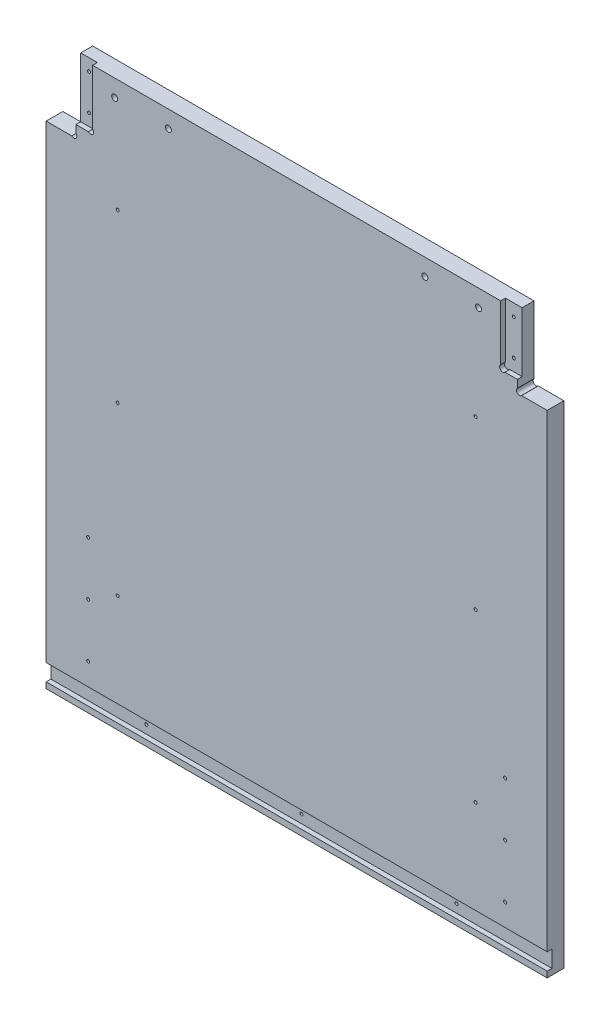
SolidWorks part; units mm, degrees
material "Pine"
ref_plane "Front Plane" through (0, 0, 0) normal (0, 0, 1) x (1, 0, 0)
ref_plane "Top Plane" through (0, 0, 0) normal (0, 1, 0) x (1, 0, 0)
ref_plane "Right Plane" through (0, 0, 0) normal (1, 0, 0) x (0, 0, -1)
sketch "Sketch1" plane through (0, 0, 0) normal (0, 0, 1) x (1, 0, 0)
  line L0 (8932.6508, -5243.5125) -> (10226.1458, -5243.5125)
  line L1 (9086.3208, -4722.0918) -> (10222.9708, -4853.7812)
  line L2 (8914.8708, -6342.0625) -> (10197.5708, -6342.0625)
  line L3 (8914.8708, -5808.6625) -> (10197.5708, -5808.6625)
  line L4 (8919.6333, -5253.0375) -> (10218.2083, -5253.0375)
  line L5 (9134.2633, -4656.1375) -> (9134.2633, -4638.3575)
  line L6 (9091.0833, -4638.3575) -> (9134.2633, -4638.3575)
  line L7 (9091.0833, -4567.2375) -> (9091.0833, -4638.3575)
  line L8 (9134.2633, -4656.1375) -> (9581.3033, -4656.1375)
  line L9 (9091.0833, -4567.2375) -> (9624.4833, -4567.2375)
  line L10 (9581.3033, -4656.1375) -> (9581.3033, -4638.3575)
  line L11 (9581.3033, -4638.3575) -> (9624.4833, -4638.3575)
  line L12 (9624.4833, -4567.2375) -> (9624.4833, -4638.3575)
  line L13 (8932.6508, -5225.7325) -> (9344.9775, -5225.7325)
  line L14 (8932.6508, -5256.2125) -> (8932.6508, -5243.5125)
  line L15 (8911.6958, -5256.2125) -> (8932.6508, -5256.2125)
  line L16 (8914.8708, -4722.0918) -> (9086.3208, -4722.0918)
  line L17 (8911.6958, -4715.5913) -> (8932.6508, -4715.5913)
  line L18 (8914.8708, -6342.0625) -> (8914.8708, -5808.6625)
  line L19 (12082.9917, -4722.0918) -> (10946.3417, -4853.7812)
  line L20 (12236.6617, -5243.5125) -> (10943.1667, -5243.5125)
  line L21 (10951.1042, -5253.0375) -> (12249.6792, -5253.0375)
  line L22 (10838.3917, -5656.2625) -> (11308.2917, -5656.2625)
  line L23 (10838.3917, -5719.7625) -> (11308.2917, -5719.7625)
  line L24 (10838.3917, -5742.5368) -> (11308.2917, -5742.5368)
  line L25 (10806.6417, -6342.0625) -> (11340.0417, -6342.0625)
  line L26 (10803.4667, -6335.7125) -> (11343.2167, -6335.7125)
  line L27 (10803.4667, -6317.9325) -> (11343.2167, -6317.9325)
  line L28 (10943.1667, -5225.7325) -> (11376.4483, -5225.7325)
  line L29 (11506.7292, -4754.5625) -> (10806.6417, -4827.5875)
  line L30 (11506.7292, -4567.2375) -> (11506.7292, -4754.5625)
  line L31 (10806.6417, -4567.2375) -> (10806.6417, -4827.5875)
  line L32 (10806.6417, -4567.2375) -> (11506.7292, -4567.2375)
  line L33 (10235.6708, -6329.3625) -> (10245.1958, -6329.3625)
  line L34 (10245.1958, -6329.3625) -> (10254.7208, -6278.5625)
  line L35 (10302.3458, -6329.3625) -> (10311.8708, -6278.5625)
  line L36 (10302.3458, -6329.3625) -> (10292.8208, -6329.3625)
  line L37 (10245.1958, -5821.3625) -> (10254.7208, -5872.1625)
  line L38 (10235.6708, -5821.3625) -> (10245.1958, -5821.3625)
  line L39 (10292.8208, -5821.3625) -> (10302.3458, -5821.3625)
  line L40 (10302.3458, -5821.3625) -> (10311.8708, -5872.1625)
  line L41 (10235.6708, -5821.3625) -> (10235.6708, -6329.3625)
  line L42 (10254.7208, -5872.1625) -> (10254.7208, -6278.5625)
  line L43 (10311.8708, -5872.1625) -> (10311.8708, -6278.5625)
  line L44 (10292.8208, -5821.3625) -> (10292.8208, -6329.3625)
  line L45 (8932.6508, -5225.7325) -> (8932.6508, -4715.5913)
  line L46 (8911.6958, -4715.5913) -> (8911.6958, -5256.2125)
  line L47 (8914.8708, -5248.275) -> (8914.8708, -4722.0918)
  line L48 (8919.6333, -5253.0375) -> (8914.8708, -5248.275)
  line L49 (8914.8708, -5145.0875) -> (8937.426, -5145.0875)
  line L50 (8914.8708, -5202.2375) -> (8937.426, -5202.2375)
  line L51 (10838.3917, -5656.2625) -> (10838.3917, -5719.7625)
  line L52 (10832.0417, -5736.1868) -> (10856.1717, -5736.1868)
  line L53 (10806.6417, -6342.0625) -> (10806.6417, -5818.7368)
  line L54 (10832.0417, -5649.9125) -> (10856.1717, -5649.9125)
  line L55 (10832.0417, -5726.1125) -> (10856.1717, -5726.1125)
  line L56 (10806.6417, -5818.7368) -> (10833.9015, -5818.7368)
  line L57 (10832.0417, -5806.0442) -> (10851.6815, -5806.0442)
  line L58 (10856.1717, -5801.5541) -> (10856.1717, -5736.1868)
  line L59 (10838.3917, -5814.2467) -> (10838.3917, -5742.5368)
  line L60 (10832.0417, -5806.0442) -> (10832.0417, -5736.1868)
  line L61 (10803.4667, -6317.9325) -> (10803.4667, -6335.7125)
  line L62 (10197.5708, -5808.6625) -> (10197.5708, -6342.0625)
  line L63 (9762.3842, -6348.4125) -> (9762.3842, -5802.3125)
  line L64 (9780.1642, -6348.4125) -> (9762.3842, -6348.4125)
  line L65 (9780.1642, -5802.3125) -> (9780.1642, -6348.4125)
  line L66 (9762.3842, -5802.3125) -> (9780.1642, -5802.3125)
  line L67 (9332.2775, -6348.4125) -> (9332.2775, -5802.3125)
  line L68 (9332.2775, -6348.4125) -> (9350.0575, -6348.4125)
  line L69 (9350.0575, -5802.3125) -> (9350.0575, -6348.4125)
  line L70 (9332.2775, -5802.3125) -> (9350.0575, -5802.3125)
  line L71 (9993.8374, -6061.075) -> (9993.8374, -6045.2418)
  line L72 (9998.5999, -6065.8375) -> (10014.4331, -6065.8375)
  line L73 (9998.5999, -6084.8875) -> (10014.4331, -6084.8875)
  line L74 (9993.8374, -6105.4832) -> (9993.8374, -6089.65)
  line L75 (9974.7874, -6105.4832) -> (9974.7874, -6089.65)
  line L76 (9954.1917, -6084.8875) -> (9970.0249, -6084.8875)
  line L77 (9974.7874, -6061.075) -> (9974.7874, -6045.2418)
  line L78 (9954.1917, -6065.8375) -> (9970.0249, -6065.8375)
  line L79 (10793.9417, -6237.2875) -> (10816.4969, -6237.2875)
  line L80 (10793.9417, -6294.4375) -> (10816.4969, -6294.4375)
  line L81 (10856.1717, -5649.9125) -> (10856.1717, -5726.1125)
  line L82 (10832.0417, -5726.1125) -> (10832.0417, -5649.9125)
  line L83 (10226.1458, -5225.7325) -> (10226.1458, -5243.5125)
  line L84 (10205.1908, -5257.8) -> (10205.1908, -4844.2499)
  line L85 (10230.9083, -4844.2499) -> (10230.9083, -5257.8)
  line L86 (10205.1908, -5257.8) -> (10230.9083, -5257.8)
  line L87 (10205.1908, -4844.2499) -> (10230.9083, -4844.2499)
  line L88 (10946.3417, -5176.8375) -> (10968.8969, -5176.8375)
  line L89 (9349.4676, -5141.9125) -> (9358.2674, -5141.9125)
  line L90 (10946.3417, -5119.6875) -> (10968.8969, -5119.6875)
  line L91 (9929.011, -4660.9635) -> (10066.0807, -4660.9635)
  line L92 (9929.011, -4678.7435) -> (10066.0807, -4678.7435)
  line L93 (10943.1667, -5225.7325) -> (10943.1667, -5243.5125)
  line L94 (10946.3417, -5248.275) -> (10951.1042, -5253.0375)
  line L95 (10946.3417, -5257.8063) -> (10946.3417, -4849.0188)
  line L96 (10964.1217, -5257.8) -> (10964.1217, -4844.2499)
  line L97 (10938.4042, -4844.2499) -> (10938.4042, -5257.8)
  line L98 (10938.4042, -5257.8) -> (10964.1217, -5257.8)
  line L99 (10964.1217, -4844.2499) -> (10938.4042, -4844.2499)
  line L100 (10344.8908, -4560.8875) -> (10369.0208, -4560.8875)
  line L101 (10344.8908, -4560.8875) -> (10369.0208, -4560.8875)
  line L102 (10800.2917, -4560.8875) -> (10824.4217, -4560.8875)
  line L103 (10200.4156, -5119.6875) -> (10222.9708, -5119.6875)
  line L104 (10200.4156, -5176.8375) -> (10222.9708, -5176.8375)
  line L105 (9344.9775, -5146.4026) -> (9344.9775, -5225.7325)
  line L106 (10344.8908, -4560.8875) -> (10344.8908, -4833.9375)
  line L107 (9792.8642, -5225.7325) -> (9792.8642, -5146.4026)
  line L108 (9362.7575, -5225.7325) -> (9775.0842, -5225.7325)
  line L109 (9680.3633, -4761.8396) -> (9680.3633, -4559.9604)
  line L110 (9656.2333, -4559.9604) -> (9680.3633, -4559.9604)
  line L111 (9656.2333, -4761.8396) -> (9680.3633, -4761.8396)
  line L112 (9656.2333, -4761.8396) -> (9656.2333, -4559.9604)
  line L113 (9779.5743, -5141.9125) -> (9788.374, -5141.9125)
  line L114 (10070.5708, -4665.4536) -> (10070.5708, -4674.2534)
  line L115 (9924.5208, -4674.2534) -> (9924.5208, -4665.4536)
  line L116 (12127.4417, -6188.3925) -> (12205.5015, -6188.3925)
  line L117 (12209.9917, -6170.6125) -> (12209.9917, -6183.9024)
  line L118 (9792.8642, -5225.7325) -> (10226.1458, -5225.7325)
  line L119 (9662.5833, -4754.5625) -> (10362.6708, -4827.5875)
  line L120 (9662.5833, -4567.2375) -> (9662.5833, -4754.5625)
  line L121 (10362.6708, -4567.2375) -> (10362.6708, -4827.5875)
  line L122 (9662.5833, -4567.2375) -> (10362.6708, -4567.2375)
  line L123 (10824.4217, -4833.9375) -> (10800.2917, -4833.9375)
  line L124 (10800.2917, -4833.9375) -> (10800.2917, -4560.8875)
  line L125 (10824.4217, -4560.8875) -> (10824.4217, -4833.9375)
  line L126 (10344.8908, -4833.9375) -> (10369.0208, -4833.9375)
  line L127 (10369.0208, -4833.9375) -> (10369.0208, -4560.8875)
  line L128 (10222.9708, -5248.275) -> (10218.2083, -5253.0375)
  line L129 (10222.9708, -5257.8063) -> (10222.9708, -4849.0188)
  line L130 (11734.6544, -5701.375) -> (11739.2301, -5701.375)
  line L131 (9362.7575, -5225.7325) -> (9362.7575, -5146.4026)
  line L132 (9775.0842, -5146.4026) -> (9775.0842, -5225.7325)
  line L133 (11761.3864, -5701.375) -> (11756.8282, -5701.375)
  line L134 (11734.6544, -5693.755) -> (11739.2301, -5693.755)
  line L135 (11761.4039, -5693.755) -> (11756.8282, -5693.755)
  line L136 (11734.6544, -5701.375) -> (11739.2301, -5701.375)
  line L137 (11744.3462, -5721.3024) -> (11744.3462, -5706.4179)
  line L138 (11751.7122, -5721.3024) -> (11751.7122, -5706.4179)
  line L139 (11740.0917, -6170.6125) -> (11740.0917, -6183.9024)
  line L140 (11689.2917, -6188.3925) -> (11822.6417, -6188.3925)
  line L141 (11689.2917, -6348.4093) -> (11689.2917, -6164.2657)
  line L142 (11689.2917, -6164.2657) -> (11746.4417, -6164.2657)
  line L143 (11746.4417, -6164.2657) -> (11746.4417, -6188.3925)
  line L144 (11689.2917, -6164.2657) -> (11746.4417, -6164.2657)
  line L145 (11340.0417, -5818.7368) -> (11340.0417, -6342.0625)
  line L146 (11290.5117, -5726.1125) -> (11314.6417, -5726.1125)
  line L147 (11290.5117, -5649.9125) -> (11290.5117, -5726.1125)
  line L148 (11340.0417, -5818.7368) -> (11312.7818, -5818.7368)
  line L149 (11314.6417, -5806.0442) -> (11295.0018, -5806.0442)
  line L150 (11290.5117, -5801.5541) -> (11290.5117, -5736.1868)
  line L151 (11308.2917, -5814.2467) -> (11308.2917, -5742.5368)
  line L152 (11314.6417, -5806.0442) -> (11314.6417, -5736.1868)
  line L153 (11290.5117, -5736.1868) -> (11314.6417, -5736.1868)
  line L154 (11848.0417, -6267.1325) -> (11962.3417, -6267.1325)
  line L155 (11962.3417, -6267.1325) -> (11962.3417, -6203.6325)
  line L156 (11343.2167, -6317.9325) -> (11343.2167, -6335.7125)
  line L157 (11365.4417, -5656.2625) -> (11365.4417, -5719.7625)
  line L158 (11365.4417, -5656.2625) -> (11479.7417, -5656.2625)
  line L159 (11778.1917, -6071.3937) -> (11802.3217, -6071.3937)
  line L160 (11314.6417, -5726.1125) -> (11314.6417, -5649.9125)
  line L161 (11314.6417, -5649.9125) -> (11290.5117, -5649.9125)
  line L162 (11308.2917, -5719.7625) -> (11308.2917, -5656.2625)
  line L163 (11689.2917, -6348.4093) -> (11713.4217, -6348.4093)
  line L164 (12203.6417, -6164.2657) -> (12260.7917, -6164.2657)
  line L165 (11713.4217, -6348.4093) -> (11713.4217, -6164.2657)
  line L166 (11695.6417, -6342.0625) -> (11695.6417, -6170.6125)
  line L167 (11695.6417, -6048.5337) -> (11699.4517, -6052.3437)
  line L168 (11822.6417, -6292.5325) -> (11822.6417, -6188.3925)
  line L169 (11695.6417, -6342.0625) -> (11695.6417, -6170.6125)
  line L170 (11848.0417, -6203.6325) -> (11962.3417, -6203.6325)
  line L171 (11848.0417, -6203.6325) -> (11848.0417, -6267.1325)
  line L172 (11987.7417, -6267.1325) -> (11987.7417, -6203.6325)
  line L173 (11784.5417, -6077.7437) -> (11784.5417, -6141.2438)
  line L174 (11517.8417, -5656.2625) -> (11632.1417, -5656.2625)
  line L175 (11632.1417, -5656.2625) -> (11632.1417, -5719.7625)
  line L176 (11632.1417, -5719.7625) -> (11517.8417, -5719.7625)
  line L177 (11517.8417, -5719.7625) -> (11517.8417, -5656.2625)
  line L178 (11692.4667, -6028.2137) -> (11692.4667, -6045.9937)
  line L179 (11695.6417, -5979.3188) -> (11718.1969, -5979.3188)
  line L180 (11695.6417, -5922.1687) -> (11718.1969, -5922.1687)
  line L181 (11821.0415, -5722.9375) -> (11821.0415, -5943.6)
  line L182 (11687.7042, -5651.5) -> (11701.9917, -5651.5)
  line L183 (11687.7042, -5651.5) -> (11687.7042, -6055.5251)
  line L184 (11687.7042, -6055.5251) -> (11701.9917, -6055.5251)
  line L185 (11701.9917, -6055.5251) -> (11701.9917, -5651.5)
  line L186 (11695.6417, -6055.2013) -> (11695.6417, -5649.595)
  line L187 (11695.6417, -5656.2625) -> (11695.6417, -6048.5337)
  line L188 (11695.6417, -6170.6125) -> (11740.0917, -6170.6125)
  line L189 (12203.6417, -6164.2657) -> (12203.6417, -6188.3925)
  line L190 (12254.4417, -6342.0625) -> (12254.4417, -6170.6125)
  line L191 (12129.0419, -5943.6) -> (12129.0419, -5722.9375)
  line L192 (12254.4417, -6048.5337) -> (12250.6317, -6052.3437)
  line L193 (12257.6167, -6045.9937) -> (12257.6167, -6028.2137)
  line L194 (12248.0917, -5651.5) -> (12262.3792, -5651.5)
  line L195 (12262.3792, -5651.5) -> (12262.3792, -6055.5251)
  line L196 (12262.3792, -6055.5251) -> (12248.0917, -6055.5251)
  line L197 (12248.0917, -6055.5251) -> (12248.0917, -5651.5)
  line L198 (12254.4417, -6141.2438) -> (12254.4417, -6077.7437)
  line L199 (12236.6617, -6164.2657) -> (12260.7917, -6164.2657)
  line L200 (12102.0417, -6267.1325) -> (11987.7417, -6267.1325)
  line L201 (11330.1865, -6237.2875) -> (11352.7417, -6237.2875)
  line L202 (11330.1865, -6294.4375) -> (11352.7417, -6294.4375)
  line L203 (11474.6617, -5851.8425) -> (11492.4417, -5851.8425)
  line L204 (11474.6617, -5808.6625) -> (11474.6617, -5851.8425)
  line L205 (11403.5417, -5808.6625) -> (11474.6617, -5808.6625)
  line L206 (11492.4417, -5851.8425) -> (11492.4417, -6298.8825)
  line L207 (11403.5417, -6342.0625) -> (11403.5417, -5808.6625)
  line L208 (11474.6617, -6298.8825) -> (11492.4417, -6298.8825)
  line L209 (11474.6617, -6342.0625) -> (11474.6617, -6298.8825)
  line L210 (11403.5417, -6342.0625) -> (11474.6617, -6342.0625)
  line L211 (11619.4417, -5851.8425) -> (11601.6617, -5851.8425)
  line L212 (11601.6617, -5808.6625) -> (11601.6617, -5851.8425)
  line L213 (11530.5417, -5808.6625) -> (11601.6617, -5808.6625)
  line L214 (11619.4417, -5851.8425) -> (11619.4417, -6298.8825)
  line L215 (11530.5417, -6342.0625) -> (11530.5417, -5808.6625)
  line L216 (11619.4417, -6298.8825) -> (11601.6617, -6298.8825)
  line L217 (11601.6617, -6342.0625) -> (11601.6617, -6298.8825)
  line L218 (11530.5417, -6342.0625) -> (11601.6617, -6342.0625)
  line L219 (11479.7417, -5719.7625) -> (11479.7417, -5656.2625)
  line L220 (11365.4417, -5719.7625) -> (11479.7417, -5719.7625)
  line L221 (11778.1917, -6147.5937) -> (11802.3217, -6147.5937)
  line L222 (11802.3217, -6071.3937) -> (11802.3217, -6147.5937)
  line L223 (11778.1917, -6147.5937) -> (11778.1917, -6071.3937)
  line L224 (12254.4417, -5922.1687) -> (12231.8865, -5922.1687)
  line L225 (12254.4417, -5979.3188) -> (12231.8865, -5979.3188)
  line L226 (12254.4417, -6055.2013) -> (12254.4417, -5649.595)
  line L227 (12254.4417, -6048.5337) -> (12254.4417, -5656.2625)
  line L228 (11841.6917, -5702.2873) -> (12108.3917, -5702.2873)
  line L229 (11822.6417, -6292.5325) -> (12127.4417, -6292.5325)
  line L230 (12127.4417, -6292.5325) -> (12127.4417, -6188.3925)
  line L231 (12254.4417, -6170.6125) -> (12209.9917, -6170.6125)
  line L232 (11695.6417, -6342.0625) -> (12254.4417, -6342.0625)
  line L233 (12236.6617, -6348.4093) -> (12260.7917, -6348.4093)
  line L234 (12260.7917, -6348.4093) -> (12260.7917, -6164.2657)
  line L235 (12236.6617, -6348.4093) -> (12236.6617, -6164.2657)
  line L236 (12102.0417, -6203.6325) -> (12102.0417, -6267.1325)
  line L237 (11987.7417, -6203.6325) -> (12102.0417, -6203.6325)
  line L238 (12236.6617, -6147.5937) -> (12236.6617, -6071.3937)
  line L239 (12203.6417, -6188.3925) -> (12260.7917, -6188.3925)
  line L240 (11098.7417, -4665.4536) -> (11098.7417, -4674.2534)
  line L241 (11394.2283, -5146.4026) -> (11394.2283, -5225.7325)
  line L242 (11376.4483, -5225.7325) -> (11376.4483, -5146.4026)
  line L243 (11394.2283, -5225.7325) -> (11806.555, -5225.7325)
  line L244 (11841.6917, -5964.2502) -> (12108.3917, -5964.2502)
  line L245 (12236.6617, -6147.5937) -> (12260.7917, -6147.5937)
  line L246 (12236.6617, -5256.2125) -> (12236.6617, -5243.5125)
  line L247 (12260.7917, -6147.5937) -> (12260.7917, -6071.3937)
  line L248 (12260.7917, -6071.3937) -> (12236.6617, -6071.3937)
  line L249 (12254.4417, -6077.7437) -> (11784.5417, -6077.7437)
  line L250 (11784.5417, -6141.2438) -> (12254.4417, -6141.2438)
  line L252 (12254.4417, -5656.2625) -> (11695.6417, -5656.2625)
  line L253 (11699.4517, -6052.3437) -> (12250.6317, -6052.3437)
  line L254 (11692.4667, -6045.9937) -> (12257.6167, -6045.9937)
  line L255 (11692.4667, -6028.2137) -> (12257.6167, -6028.2137)
  line L256 (11824.335, -5146.4026) -> (11824.335, -5225.7325)
  line L257 (11811.0451, -5141.9125) -> (11819.8449, -5141.9125)
  line L258 (11244.7917, -4674.2534) -> (11244.7917, -4665.4536)
  line L259 (11806.555, -5225.7325) -> (11806.555, -5146.4026)
  line L260 (11488.9492, -4761.8396) -> (11488.9492, -4559.9604)
  line L261 (11488.9492, -4559.9604) -> (11513.0792, -4559.9604)
  line L262 (11488.9492, -4761.8396) -> (11513.0792, -4761.8396)
  line L263 (11513.0792, -4761.8396) -> (11513.0792, -4559.9604)
  line L264 (11240.3015, -4660.9635) -> (11103.2318, -4660.9635)
  line L265 (11103.2318, -4678.7435) -> (11240.3015, -4678.7435)
  line L266 (12236.6617, -5225.7325) -> (12236.6617, -4715.5913)
  line L267 (12257.6167, -4715.5913) -> (12257.6167, -5256.2125)
  line L268 (12254.4417, -5248.275) -> (12254.4417, -4722.0918)
  line L269 (12236.6617, -5225.7325) -> (11824.335, -5225.7325)
  line L270 (12035.0492, -4656.1375) -> (12035.0492, -4638.3575)
  line L271 (12078.2292, -4638.3575) -> (12035.0492, -4638.3575)
  line L272 (12078.2292, -4567.2375) -> (12078.2292, -4638.3575)
  line L273 (12035.0492, -4656.1375) -> (11588.0092, -4656.1375)
  line L274 (11544.8292, -4567.2375) -> (12078.2292, -4567.2375)
  line L275 (11588.0092, -4656.1375) -> (11588.0092, -4638.3575)
  line L276 (11544.8292, -4638.3575) -> (11588.0092, -4638.3575)
  line L277 (11544.8292, -4567.2375) -> (11544.8292, -4638.3575)
  line L278 (12249.6792, -5253.0375) -> (12254.4417, -5248.275)
  line L280 (12257.6167, -5256.2125) -> (12236.6617, -5256.2125)
  line L281 (12231.8865, -5145.0875) -> (12254.4417, -5145.0875)
  line L282 (12231.8865, -5202.2375) -> (12254.4417, -5202.2375)
  line L283 (12236.6617, -4715.5913) -> (12257.6167, -4715.5913)
  line L284 (12082.9917, -4722.0918) -> (12254.4417, -4722.0918)
  line L285 (11380.9385, -5141.9125) -> (11389.7382, -5141.9125)
  circle A0 centre (8923.7608, -4778.9042) radius 1.5875
  circle A1 centre (9062.6598, -4736.3765) radius 2.3685
  circle A2 centre (9051.3958, -6281.7375) radius 22.225
  circle A3 centre (9083.1458, -6249.9875) radius 1.5875
  circle A4 centre (9083.1458, -6313.4875) radius 1.5875
  circle A5 centre (9019.6458, -6249.9875) radius 1.5875
  circle A6 centre (9019.6458, -6313.4875) radius 1.5875
  circle A7 centre (8972.3383, -5202.2375) radius 1.5875
  circle A8 centre (8923.7608, -5015.9708) radius 1.5875
  circle A9 centre (8923.7608, -5134.5042) radius 1.5875
  circle A10 centre (9054.5708, -5234.6225) radius 1.5875
  circle A11 centre (8923.7608, -4897.4375) radius 1.5875
  circle A12 centre (8972.3383, -5087.9375) radius 1.5875
  circle A13 centre (8972.3383, -5145.0875) radius 1.5875
  circle A14 centre (10847.2817, -5668.9625) radius 1.5875
  circle A15 centre (10847.2817, -5707.0625) radius 1.5875
  circle A16 centre (10847.2817, -5755.2368) radius 1.5875
  circle A17 centre (10851.4092, -6237.2875) radius 1.5875
  circle A18 centre (10851.4092, -6294.4375) radius 1.5875
  circle A19 centre (10847.2817, -5793.3442) radius 1.5875
  arc A20 (10833.9015, -5818.7368) -> (10838.3917, -5814.2467) centre (10836.1466, -5816.4918) ccw
  arc A21 (10851.6815, -5806.0442) -> (10856.1717, -5801.5541) centre (10853.9266, -5803.7992) ccw
  circle A22 centre (10882.8417, -6040.4375) radius 1.5875
  circle A23 centre (10882.8417, -6218.2375) radius 1.5875
  circle A24 centre (10882.8417, -5862.6375) radius 1.5875
  circle A25 centre (10908.2417, -6326.8225) radius 1.5875
  circle A26 centre (10908.2417, -6326.8225) radius 1.5875
  circle A27 centre (10851.4092, -6180.1375) radius 1.5875
  circle A28 centre (10815.5317, -4783.4231) radius 1.5875
  circle A29 centre (10815.5317, -4696.9488) radius 1.5875
  circle A30 centre (10815.5317, -4610.4746) radius 1.5875
  circle A31 centre (10979.1323, -4867.0082) radius 2.3685
  circle A32 centre (10190.1802, -4867.0082) radius 2.3685
  circle A33 centre (10955.2317, -4929.9812) radius 1.5875
  circle A34 centre (10955.2317, -5031.5812) radius 1.5875
  circle A35 centre (10214.0808, -4929.9812) radius 1.5875
  circle A36 centre (10214.0808, -5031.5812) radius 1.5875
  circle A37 centre (9341.1675, -6265.8625) radius 1.5875
  circle A38 centre (9771.2742, -5884.8625) radius 1.5875
  circle A39 centre (9771.2742, -6138.8625) radius 1.5875
  circle A40 centre (9771.2742, -6011.8625) radius 1.5875
  arc A41 (10036.2287, -6113.8083) -> (10051.3426, -6111.6033) centre (10042.9639, -6107.0732) ccw
  arc A42 (10051.3426, -6111.6033) -> (10051.3426, -6039.1217) centre (9984.3124, -6075.3625) ccw
  arc A43 (10051.3426, -6039.1217) -> (10036.2287, -6036.9167) centre (10042.9639, -6043.6518) ccw
  arc A44 (10034.5851, -6102.5431) -> (10034.5851, -6048.1819) centre (9984.3124, -6075.3625) ccw
  arc A45 (10034.5851, -6102.5431) -> (10036.2287, -6113.8083) centre (10042.9639, -6107.0732) ccw
  arc A46 (10036.2287, -6036.9167) -> (10034.5851, -6048.1819) centre (10042.9639, -6043.6518) ccw
  arc A47 (9945.8666, -6127.2787) -> (9948.0717, -6142.3927) centre (9952.6018, -6134.0139) ccw
  arc A48 (9948.0717, -6142.3927) -> (10020.5532, -6142.3927) centre (9984.3124, -6075.3625) ccw
  arc A49 (10020.5532, -6142.3927) -> (10022.7583, -6127.2787) centre (10016.0231, -6134.0139) ccw
  arc A50 (9957.1319, -6125.6352) -> (10011.493, -6125.6352) centre (9984.3124, -6075.3625) ccw
  arc A51 (9957.1319, -6125.6352) -> (9945.8666, -6127.2787) centre (9952.6018, -6134.0139) ccw
  arc A52 (10022.7583, -6127.2787) -> (10011.493, -6125.6352) centre (10016.0231, -6134.0139) ccw
  arc A53 (9932.3962, -6036.9167) -> (9917.2822, -6039.1217) centre (9925.661, -6043.6518) ccw
  arc A54 (9917.2822, -6039.1217) -> (9917.2822, -6111.6033) centre (9984.3124, -6075.3625) ccw
  arc A55 (9917.2822, -6111.6033) -> (9932.3962, -6113.8083) centre (9925.661, -6107.0732) ccw
  arc A56 (9934.0398, -6048.1819) -> (9934.0398, -6102.5431) centre (9984.3124, -6075.3625) ccw
  arc A57 (9934.0398, -6048.1819) -> (9932.3962, -6036.9167) centre (9925.661, -6043.6518) ccw
  arc A58 (9932.3962, -6113.8083) -> (9934.0398, -6102.5431) centre (9925.661, -6107.0732) ccw
  arc A59 (9945.8666, -6023.4463) -> (9957.1319, -6025.0898) centre (9952.6018, -6016.7111) ccw
  arc A60 (10011.493, -6025.0898) -> (10022.7583, -6023.4463) centre (10016.0231, -6016.7111) ccw
  arc A61 (10011.493, -6025.0898) -> (9957.1319, -6025.0898) centre (9984.3124, -6075.3625) ccw
  arc A62 (9948.0717, -6008.3323) -> (9945.8666, -6023.4463) centre (9952.6018, -6016.7111) ccw
  arc A63 (10020.5532, -6008.3323) -> (9948.0717, -6008.3323) centre (9984.3124, -6075.3625) ccw
  arc A64 (10022.7583, -6023.4463) -> (10020.5532, -6008.3323) centre (10016.0231, -6016.7111) ccw
  arc A65 (10005.0943, -6187.7574) -> (10096.7073, -6096.1443) centre (9984.3124, -6075.3625) ccw
  arc A66 (9993.8374, -6178.3911) -> (10005.0943, -6187.7574) centre (10003.3624, -6178.3911) ccw
  arc A67 (10001.6306, -6169.0249) -> (10077.9748, -6092.6807) centre (9984.3124, -6075.3625) ccw
  arc A68 (10087.3411, -6084.8875) -> (10077.9748, -6092.6807) centre (10087.3411, -6094.4125) ccw
  arc A69 (10001.6306, -6169.0249) -> (9993.8374, -6178.3911) centre (10003.3624, -6178.3911) ccw
  arc A70 (9963.5306, -6187.7574) -> (9974.7874, -6178.3911) centre (9965.2624, -6178.3911) ccw
  arc A71 (9871.9176, -6096.1443) -> (9963.5306, -6187.7574) centre (9984.3124, -6075.3625) ccw
  arc A72 (9881.2838, -6084.8875) -> (9871.9176, -6096.1443) centre (9881.2838, -6094.4125) ccw
  arc A73 (9890.65, -6092.6807) -> (9966.9943, -6169.0249) centre (9984.3124, -6075.3625) ccw
  arc A74 (9974.7874, -6178.3911) -> (9966.9943, -6169.0249) centre (9965.2624, -6178.3911) ccw
  arc A75 (9890.65, -6092.6807) -> (9881.2838, -6084.8875) centre (9881.2838, -6094.4125) ccw
  arc A76 (9871.9176, -6054.5807) -> (9881.2838, -6065.8375) centre (9881.2838, -6056.3125) ccw
  arc A77 (9963.5306, -5962.9676) -> (9871.9176, -6054.5807) centre (9984.3124, -6075.3625) ccw
  arc A78 (9974.7874, -5972.3339) -> (9963.5306, -5962.9676) centre (9965.2624, -5972.3339) ccw
  arc A79 (9966.9943, -5981.7001) -> (9890.65, -6058.0443) centre (9984.3124, -6075.3625) ccw
  arc A80 (9881.2838, -6065.8375) -> (9890.65, -6058.0443) centre (9881.2838, -6056.3125) ccw
  arc A81 (9966.9943, -5981.7001) -> (9974.7874, -5972.3339) centre (9965.2624, -5972.3339) ccw
  arc A82 (10077.9748, -6058.0443) -> (10087.3411, -6065.8375) centre (10087.3411, -6056.3125) ccw
  arc A83 (9993.8374, -5972.3339) -> (10001.6306, -5981.7001) centre (10003.3624, -5972.3339) ccw
  arc A84 (10077.9748, -6058.0443) -> (10001.6306, -5981.7001) centre (9984.3124, -6075.3625) ccw
  arc A85 (10087.3411, -6065.8375) -> (10096.7073, -6054.5807) centre (10087.3411, -6056.3125) ccw
  arc A86 (10096.7073, -6054.5807) -> (10005.0943, -5962.9676) centre (9984.3124, -6075.3625) ccw
  arc A87 (10005.0943, -5962.9676) -> (9993.8374, -5972.3339) centre (10003.3624, -5972.3339) ccw
  arc A88 (10014.4331, -6065.8375) -> (10018.7361, -6059.0339) centre (10014.4331, -6061.075) ccw
  arc A89 (10018.7361, -6059.0339) -> (10000.641, -6040.9388) centre (9984.3124, -6075.3625) ccw
  arc A90 (10000.641, -6040.9388) -> (9993.8374, -6045.2418) centre (9998.5999, -6045.2418) ccw
  arc A91 (9993.8374, -6061.075) -> (9998.5999, -6065.8375) centre (9998.5999, -6061.075) ccw
  arc A92 (9993.8374, -6105.4832) -> (10000.641, -6109.7862) centre (9998.5999, -6105.4832) ccw
  arc A93 (10000.641, -6109.7862) -> (10018.7361, -6091.6911) centre (9984.3124, -6075.3625) ccw
  arc A94 (10018.7361, -6091.6911) -> (10014.4331, -6084.8875) centre (10014.4331, -6089.65) ccw
  arc A95 (9998.5999, -6084.8875) -> (9993.8374, -6089.65) centre (9998.5999, -6089.65) ccw
  arc A96 (9954.1917, -6084.8875) -> (9949.8888, -6091.6911) centre (9954.1917, -6089.65) ccw
  arc A97 (9949.8888, -6091.6911) -> (9967.9839, -6109.7862) centre (9984.3124, -6075.3625) ccw
  arc A98 (9967.9839, -6109.7862) -> (9974.7874, -6105.4832) centre (9970.0249, -6105.4832) ccw
  arc A99 (9974.7874, -6089.65) -> (9970.0249, -6084.8875) centre (9970.0249, -6089.65) ccw
  arc A100 (9970.0249, -6065.8375) -> (9974.7874, -6061.075) centre (9970.0249, -6061.075) ccw
  arc A101 (9949.8888, -6059.0339) -> (9954.1917, -6065.8375) centre (9954.1917, -6061.075) ccw
  arc A102 (9967.9839, -6040.9388) -> (9949.8888, -6059.0339) centre (9984.3124, -6075.3625) ccw
  arc A103 (9974.7874, -6045.2418) -> (9967.9839, -6040.9388) centre (9970.0249, -6045.2418) ccw
  arc A104 (10096.7073, -6096.1443) -> (10087.3411, -6084.8875) centre (10087.3411, -6094.4125) ccw
  circle A105 centre (9771.2742, -6265.8625) radius 1.5875
  circle A106 centre (9341.1675, -5884.8625) radius 1.5875
  circle A107 centre (9341.1675, -6138.8625) radius 1.5875
  circle A108 centre (9341.1675, -6011.8625) radius 1.5875
  circle A109 centre (11037.2315, -4887.5494) radius 15.0812
  arc A110 (9349.4676, -5141.9125) -> (9344.9775, -5146.4026) centre (9347.2226, -5144.1576) ccw
  arc A111 (9362.7575, -5146.4026) -> (9358.2674, -5141.9125) centre (9360.5124, -5144.1576) ccw
  circle A112 centre (9946.7458, -4669.8535) radius 1.5875
  arc A113 (9924.5208, -4674.2534) -> (9929.011, -4678.7435) centre (9926.7659, -4676.4984) ccw
  circle A114 centre (11003.8092, -5176.8375) radius 1.5875
  circle A115 centre (11003.8092, -5119.6875) radius 1.5875
  circle A116 centre (10353.7808, -4696.9488) radius 1.5875
  circle A117 centre (10353.7808, -4610.4746) radius 1.5875
  circle A118 centre (10353.7808, -4783.4231) radius 1.5875
  circle A119 centre (11003.8092, -5062.5375) radius 1.5875
  circle A120 centre (9353.8675, -5160.9625) radius 1.5875
  circle A121 centre (9638.7708, -5234.6225) radius 1.5875
  circle A122 centre (9671.4733, -4724.1144) radius 1.5875
  circle A123 centre (9671.4733, -4661.3637) radius 1.5875
  circle A124 centre (9671.4733, -4598.6129) radius 1.5875
  arc A125 (9792.8642, -5146.4026) -> (9788.374, -5141.9125) centre (9790.6191, -5144.1576) ccw
  arc A126 (9779.5743, -5141.9125) -> (9775.0842, -5146.4026) centre (9777.3292, -5144.1576) ccw
  circle A127 centre (10048.3458, -4669.8535) radius 1.5875
  arc A128 (10070.5708, -4665.4536) -> (10066.0807, -4660.9635) centre (10068.3258, -4663.2086) ccw
  arc A129 (10066.0807, -4678.7435) -> (10070.5708, -4674.2534) centre (10068.3258, -4676.4984) ccw
  circle A130 centre (9997.5458, -4669.8535) radius 1.5875
  arc A131 (9929.011, -4660.9635) -> (9924.5208, -4665.4536) centre (9926.7659, -4663.2086) ccw
  circle A132 centre (10132.081, -4887.5494) radius 15.0812
  circle A133 centre (10165.5033, -5176.8375) radius 1.5875
  circle A134 centre (10165.5033, -5119.6875) radius 1.5875
  circle A135 centre (9486.3708, -5234.6225) radius 1.5875
  circle A136 centre (10165.5033, -5062.5375) radius 1.5875
  circle A137 centre (9206.9708, -5234.6225) radius 1.5875
  circle A138 centre (10070.5708, -5234.6225) radius 1.5875
  circle A139 centre (9918.1708, -5234.6225) radius 1.5875
  circle A140 centre (9783.9742, -5160.9625) radius 1.5875
  circle A141 centre (9783.9742, -5193.9825) radius 1.5875
  circle A142 centre (9353.8675, -5193.9825) radius 1.5875
  circle A143 centre (11073.3417, -6326.8225) radius 1.5875
  circle A144 centre (11073.3417, -6326.8225) radius 1.5875
  circle A145 centre (11295.2742, -6180.1375) radius 1.5875
  circle A146 centre (11295.2742, -6294.4375) radius 1.5875
  circle A147 centre (11295.2742, -6237.2875) radius 1.5875
  circle A148 centre (11975.0417, -5692.775) radius 3.4925
  circle A149 centre (11263.8417, -5862.6375) radius 1.5875
  arc A150 (11739.2301, -5701.375) -> (11744.3462, -5706.4179) centre (11748.0292, -5697.565) ccw
  arc A151 (11751.7122, -5706.4179) -> (11756.8282, -5701.375) centre (11748.0292, -5697.565) ccw
  arc A152 (11744.3462, -5721.3024) -> (11751.7122, -5721.3024) centre (11748.0292, -5725.505) ccw
  arc A153 (11734.6544, -5693.755) -> (11724.9787, -5697.565) centre (11730.5667, -5697.565) ccw
  arc A154 (11756.8282, -5693.755) -> (11739.2301, -5693.755) centre (11748.0292, -5697.565) ccw
  arc A155 (11724.9787, -5697.565) -> (11734.6544, -5701.375) centre (11730.5667, -5697.565) ccw
  arc A156 (11761.3864, -5701.375) -> (11771.0797, -5697.565) centre (11765.4842, -5697.565) ccw
  arc A157 (11771.0797, -5697.565) -> (11761.4039, -5693.755) centre (11765.4917, -5697.565) ccw
  arc A158 (11740.0917, -6183.9024) -> (11744.5818, -6188.3925) centre (11742.3367, -6186.1474) ccw
  arc A159 (12205.5015, -6188.3925) -> (12209.9917, -6183.9024) centre (12207.7466, -6186.1474) ccw
  circle A160 centre (11299.4017, -5793.3442) radius 1.5875
  arc A161 (11308.2917, -5814.2467) -> (11312.7818, -5818.7368) centre (11310.5367, -5816.4918) ccw
  arc A162 (11290.5117, -5801.5541) -> (11295.0018, -5806.0442) centre (11292.7567, -5803.7992) ccw
  circle A163 centre (11704.5317, -6314.149) radius 1.5875
  circle A164 centre (11748.9817, -6208.7125) radius 1.5875
  circle A165 centre (11263.8417, -6218.2375) radius 1.5875
  circle A166 centre (11263.8417, -6040.4375) radius 1.5875
  circle A167 centre (11238.4417, -6326.8225) radius 1.5875
  circle A168 centre (11238.4417, -6326.8225) radius 1.5875
  circle A169 centre (11299.4017, -5668.9625) radius 1.5875
  circle A170 centre (11299.4017, -5707.0625) radius 1.5875
  circle A171 centre (11726.7567, -6179.5025) radius 1.5875
  circle A172 centre (11704.5317, -6199.3198) radius 1.5875
  circle A173 centre (11748.9817, -6272.2125) radius 1.5875
  circle A174 centre (11704.5317, -6256.7344) radius 1.5875
  circle A175 centre (11299.4017, -5755.2368) radius 1.5875
  circle A176 centre (11913.4467, -6301.4225) radius 1.5875
  circle A177 centre (11790.2567, -6301.4225) radius 1.5875
  circle A178 centre (11793.4317, -6128.5437) radius 1.5875
  circle A179 centre (11753.1092, -5865.0188) radius 1.5875
  circle A180 centre (11809.9417, -6037.1038) radius 1.5875
  circle A181 centre (11809.9417, -6037.1038) radius 1.5875
  circle A182 centre (11753.1092, -5922.1687) radius 1.5875
  circle A183 centre (11975.0417, -5973.7625) radius 3.4925
  circle A184 centre (11975.0417, -6037.1038) radius 1.5875
  circle A185 centre (11753.1092, -5979.3188) radius 1.5875
  circle A186 centre (11975.0417, -6037.1038) radius 1.5875
  arc A187 (11841.6917, -5702.2873) -> (11821.0415, -5722.9375) centre (11841.6917, -5722.9375) ccw
  circle A188 centre (11811.5292, -5833.2687) radius 3.4925
  arc A189 (11821.0415, -5943.6) -> (11841.6917, -5964.2502) centre (11841.6917, -5943.6) ccw
  circle A190 centre (12196.9742, -5865.0188) radius 1.5875
  arc A191 (12129.0419, -5722.9375) -> (12108.3917, -5702.2873) centre (12108.3917, -5722.9375) ccw
  circle A192 centre (12036.6367, -6301.4225) radius 1.5875
  circle A193 centre (12159.8267, -6301.4225) radius 1.5875
  circle A194 centre (12138.5542, -5833.2687) radius 3.4925
  circle A195 centre (12197.2917, -5761.0375) radius 15.0812
  circle A196 centre (11793.4317, -6090.4437) radius 1.5875
  circle A197 centre (12196.9742, -5922.1687) radius 1.5875
  arc A198 (12108.3917, -5964.2502) -> (12129.0419, -5943.6) centre (12108.3917, -5943.6) ccw
  circle A199 centre (12196.9742, -5979.3188) radius 1.5875
  circle A200 centre (12201.1017, -6272.2125) radius 1.5875
  circle A201 centre (12245.5517, -6314.149) radius 1.5875
  circle A202 centre (12245.5517, -6256.7344) radius 1.5875
  circle A203 centre (12201.1017, -6208.7125) radius 1.5875
  circle A204 centre (12223.3267, -6179.5025) radius 1.5875
  circle A205 centre (12245.5517, -6199.3198) radius 1.5875
  circle A206 centre (11171.7667, -4669.8535) radius 1.5875
  circle A207 centre (11222.5667, -4669.8535) radius 1.5875
  arc A208 (11240.3015, -4678.7435) -> (11244.7917, -4674.2534) centre (11242.5466, -4676.4984) ccw
  circle A209 centre (11385.3383, -5193.9825) radius 1.5875
  circle A210 centre (12106.6527, -4736.3765) radius 2.3685
  circle A211 centre (12140.1417, -6037.1038) radius 1.5875
  circle A212 centre (12140.1417, -6037.1038) radius 1.5875
  circle A213 centre (12245.5517, -6090.4437) radius 1.5875
  circle A214 centre (12245.5517, -6128.5437) radius 1.5875
  circle A215 centre (11385.3383, -5160.9625) radius 1.5875
  arc A216 (11824.335, -5146.4026) -> (11819.8449, -5141.9125) centre (11822.0899, -5144.1576) ccw
  arc A217 (11811.0451, -5141.9125) -> (11806.555, -5146.4026) centre (11808.8001, -5144.1576) ccw
  circle A218 centre (11815.445, -5193.9825) radius 1.5875
  circle A219 centre (11815.445, -5160.9625) radius 1.5875
  circle A220 centre (11530.5417, -5234.6225) radius 1.5875
  circle A221 centre (11962.3417, -5234.6225) radius 1.5875
  arc A222 (11244.7917, -4665.4536) -> (11240.3015, -4660.9635) centre (11242.5466, -4663.2086) ccw
  circle A223 centre (11682.9417, -5234.6225) radius 1.5875
  circle A224 centre (11497.8392, -4724.1144) radius 1.5875
  circle A225 centre (11497.8392, -4661.3637) radius 1.5875
  circle A226 centre (11497.8392, -4598.6129) radius 1.5875
  circle A227 centre (11120.9667, -4669.8535) radius 1.5875
  arc A228 (11103.2318, -4660.9635) -> (11098.7417, -4665.4536) centre (11100.9867, -4663.2086) ccw
  arc A229 (11098.7417, -4674.2534) -> (11103.2318, -4678.7435) centre (11100.9867, -4676.4984) ccw
  circle A230 centre (12196.9742, -5202.2375) radius 1.5875
  circle A231 centre (12245.5517, -5015.9708) radius 1.5875
  circle A232 centre (12245.5517, -5134.5042) radius 1.5875
  circle A233 centre (12114.7417, -5234.6225) radius 1.5875
  circle A234 centre (12245.5517, -4897.4375) radius 1.5875
  circle A235 centre (12245.5517, -4778.9042) radius 1.5875
  circle A236 centre (12196.9742, -5087.9375) radius 1.5875
  circle A237 centre (12196.9742, -5145.0875) radius 1.5875
  circle A238 centre (11098.7417, -5234.6225) radius 1.5875
  circle A239 centre (11251.1417, -5234.6225) radius 1.5875
  arc A240 (11380.9385, -5141.9125) -> (11376.4483, -5146.4026) centre (11378.6934, -5144.1576) ccw
  arc A241 (11394.2283, -5146.4026) -> (11389.7382, -5141.9125) centre (11391.9833, -5144.1576) ccw
sketch "Sketch3" plane through (0, 0, 0) normal (0, 0, 1) x (1, 0, 0)
  line L0 (10806.6417, -6342.0625) -> (11340.0417, -6342.0625)
  line L1 (11340.0417, -6342.0625) -> (11340.0417, -5818.7368)
  line L2 (11340.0417, -5818.7368) -> (11312.7818, -5818.7368)
  line L3 (11312.7818, -5818.7368) -> (11308.2917, -5814.2467)
  line L4 (11308.2917, -5814.2467) -> (11308.2917, -5742.5368)
  line L5 (10838.3917, -5742.5368) -> (10838.3917, -5814.2467)
  line L6 (10838.3917, -5814.2467) -> (10833.9015, -5818.7368)
  line L7 (10833.9015, -5818.7368) -> (10806.6417, -5818.7368)
  line L8 (10806.6417, -5818.7368) -> (10806.6417, -6342.0625)
  line L9 (10838.3917, -5742.5368) -> (11308.2917, -5742.5368)
extrude "Extrude1" add sketch "Sketch3" against normal blind 17.78
sketch "Sketch4" plane through (0, 0, 0) normal (0, 0, 1) x (1, 0, 0)
  circle A0 centre (11310.5367, -5816.4918) radius 3.175
  circle A1 centre (10836.1466, -5816.4918) radius 3.175
extrude "Cut-Extrude1" cut sketch "Sketch4" against normal up to surface (17.78 mm away) up to face at (11073.3417, -5907.2639, -17.78)
sketch "Sketch6" plane through (0, 0, 0) normal (0, 0, 1) x (1, 0, 0)
  circle A0 centre (10851.4092, -6294.4375) radius 1.5875
  circle A1 centre (10908.2417, -6326.8225) radius 1.5875
  circle A2 centre (11073.3417, -6326.8225) radius 1.5875
  circle A3 centre (11238.4417, -6326.8225) radius 1.5875
  circle A4 centre (11295.2742, -6294.4375) radius 1.5875
  circle A5 centre (11295.2742, -6237.2875) radius 1.5875
  circle A6 centre (11263.8417, -6218.2375) radius 1.5875
  circle A7 centre (11295.2742, -6180.1375) radius 1.5875
  circle A8 centre (11263.8417, -6040.4375) radius 1.5875
  circle A9 centre (11263.8417, -5862.6375) radius 1.5875
  circle A10 centre (11299.4017, -5793.3442) radius 1.5875
  circle A11 centre (11299.4017, -5755.2368) radius 1.5875
  circle A12 centre (10847.2817, -5755.2368) radius 1.5875
  circle A13 centre (10847.2817, -5793.3442) radius 1.5875
  circle A14 centre (10882.8417, -6040.4375) radius 1.5875
  circle A15 centre (10851.4092, -6180.1375) radius 1.5875
  circle A16 centre (10882.8417, -6218.2375) radius 1.5875
  circle A17 centre (10851.4092, -6237.2875) radius 1.5875
  circle A18 centre (10882.8417, -5862.6375) radius 1.5875
extrude "Cut-Extrude3" cut sketch "Sketch6" against normal up to surface (17.78 mm away) up to face at (11073.3417, -5907.713, -17.78)
sketch "Sketch5" plane through (0, 0, 0) normal (0, 0, 1) x (1, 0, 0)
  line L0 (11073.3417, -6317.9325) -> (11073.3417, -6342.0625) construction
  line L1 (10803.4667, -6317.9325) -> (11343.2167, -6317.9325) construction
  line L2 (10806.6417, -6342.0625) -> (11340.0417, -6342.0625) construction
  line L3 (11073.3417, -6317.9325) -> (10806.6417, -6317.9325)
  line L4 (10838.3917, -5742.5368) -> (10838.3917, -5806.0442)
  line L6 (11308.2917, -5742.5368) -> (11308.2917, -5806.0442)
  line L8 (10838.3917, -5806.0442) -> (10856.1717, -5806.0442)
  line L11 (11308.2917, -5806.0442) -> (11290.5117, -5806.0442)
  line L12 (10806.6417, -6342.0625) -> (10806.6417, -5818.7368) construction
  line L13 (10806.6417, -6317.9325) -> (10806.6417, -6335.7125)
  line L15 (10806.6417, -6335.7125) -> (11340.0417, -6335.7125)
  line L17 (10856.1717, -5806.0442) -> (10856.1717, -5742.5368)
  line L20 (10856.1717, -5742.5368) -> (10838.3917, -5742.5368)
  line L21 (11290.5117, -5806.0442) -> (11290.5117, -5742.5368)
  line L24 (11290.5117, -5742.5368) -> (11308.2917, -5742.5368)
  line L25 (11340.0417, -5818.7368) -> (11340.0417, -6342.0625) construction
  line L26 (11340.0417, -6317.9325) -> (11073.3417, -6317.9325)
  line L27 (11340.0417, -6335.7125) -> (11340.0417, -6317.9325)
  dimension "D1" = 17.78
  dimension "D3" = 17.78
  dimension "D4" = 17.78
extrude "Cut-Extrude2" cut sketch "Sketch5" against normal blind 5.08
sketch "Sketch7" plane through (0, 0, 0) normal (0, 0, 1) x (1, 0, 0)
  line L0 (10856.1717, -5806.0442) -> (10853.9266, -5803.7992) construction
  line L1 (11290.5117, -5806.0442) -> (11292.7567, -5803.7992) construction
  line L2 (10838.3917, -5806.0442) -> (10856.1717, -5806.0442) construction
  line L3 (11290.5117, -5806.0442) -> (11308.2917, -5806.0442) construction
  circle A0 centre (10853.9266, -5803.7992) radius 3.302
  circle A1 centre (11292.7567, -5803.7992) radius 3.302
  dimension "D1" = 45
  dimension "D2" = 3.175
  dimension "D3" = 45
  dimension "D4" = 3.175
extrude "Cut-Extrude4" cut sketch "Sketch7" against normal up to surface (5.08 mm away) up to face at (10848.8692, -5793.3442, -5.08)
sketch "Sketch9" plane through (0, 0, 0) normal (0, 0, 1) x (1, 0, 0)
  circle A0 centre (10879.6167, -5760.6443) radius 3.175
  circle A1 centre (10936.8167, -5760.6443) radius 3.175
  circle A2 centre (11209.8167, -5760.6443) radius 3.175
  circle A3 centre (11267.0167, -5760.6443) radius 3.175
extrude "Cut-Extrude5" cut sketch "Sketch9" against normal up to surface (17.78 mm away) up to face at (10884.4292, -5862.6375, -17.78)
